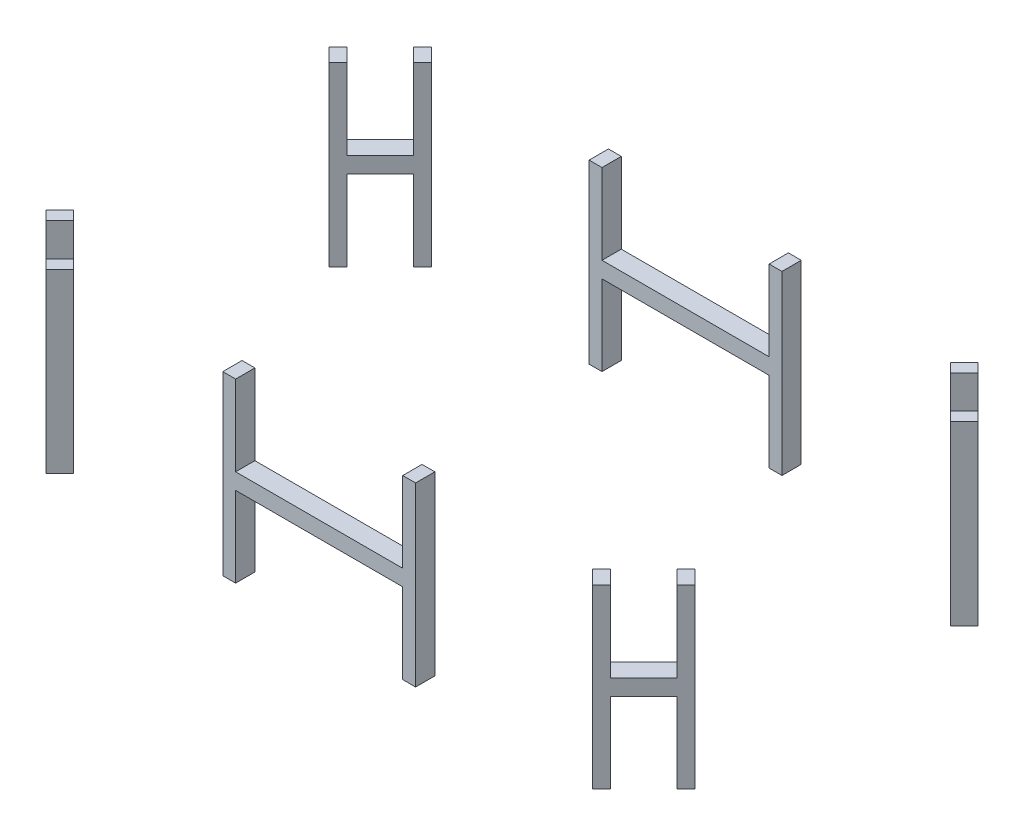
SolidWorks part; units mm, degrees
ref_plane "前视基准面" through (0, 0, 0) normal (0, 0, 1) x (1, 0, 0)
ref_plane "上视基准面" through (0, 0, 0) normal (0, 1, 0) x (1, 0, 0)
ref_plane "右视基准面" through (0, 0, 0) normal (1, 0, 0) x (0, 0, -1)
sketch "草图1" plane through (0, 0, 0) normal (0, 1, 0) x (1, 0, 0)
  line L8 (-505, 220) -> (-425, 300)
  line L12 (-425, 300) -> (-403.7868, 278.7868)
  line L13 (-403.7868, 278.7868) -> (-483.7868, 198.7868)
  line L14 (-505, 220) -> (-483.7868, 198.7868)
  line L15 (-150, 270) -> (150, 270)
  line L16 (0, 300) -> (-150, 300)
  line L17 (-150, 300) -> (-150, 270)
  line L18 (0, 300) -> (150, 300)
  line L19 (150, 300) -> (150, 270)
  line L20 (0, 0) -> (0, 106.1612) construction
  line L21 (0, 0) -> (94.5244, 0) construction
  line L22 (505, 220) -> (483.7868, 198.7868)
  line L23 (403.7868, 278.7868) -> (483.7868, 198.7868)
  line L24 (425, 300) -> (403.7868, 278.7868)
  line L25 (505, 220) -> (425, 300)
  line L26 (505, -220) -> (425, -300)
  line L27 (425, -300) -> (403.7868, -278.7868)
  line L28 (403.7868, -278.7868) -> (483.7868, -198.7868)
  line L29 (505, -220) -> (483.7868, -198.7868)
  line L30 (-150, -300) -> (-150, -270)
  line L31 (0, -300) -> (-150, -300)
  line L32 (0, -300) -> (150, -300)
  line L33 (150, -300) -> (150, -270)
  line L34 (-150, -270) -> (150, -270)
  line L35 (-505, -220) -> (-483.7868, -198.7868)
  line L36 (-403.7868, -278.7868) -> (-483.7868, -198.7868)
  line L37 (-425, -300) -> (-403.7868, -278.7868)
  line L38 (-505, -220) -> (-425, -300)
  point P3 (-505, 300)
  point P5 (505, 300)
  point P6 (505, -300)
  point P7 (-505, -300)
extrude "凸台-拉伸1" add sketch "草图1" along normal blind 275
sketch "草图2" plane through (0, 0, 300) normal (0, 0, 1) x (1, 0, 0)
  line L1 (-150, 275) -> (150, 275) construction
  line L3 (130, 275) -> (130, 150)
  line L4 (-130, 275) -> (-130, 150)
  line L5 (-130, 275) -> (130, 275)
  line L6 (130, 150) -> (-130, 150)
  line L8 (130, 0) -> (130, 125)
  line L9 (130, 125) -> (-130, 125)
  line L10 (-130, 0) -> (-130, 125)
  line L11 (-130, 0) -> (130, 0)
extrude "切除-拉伸1" cut sketch "草图2" against normal through all both and the other way through all
sketch "草图3" plane through (362.5, 0, 362.5) normal (0.7071, 0, 0.7071) x (0.7071, 0, -0.7071)
  line L1 (88.3883, 275) -> (201.5254, 275) construction
  line L2 (108.3883, 275) -> (108.3883, 150)
  line L4 (181.5254, 275) -> (181.5254, 150)
  line L5 (181.5254, 150) -> (108.3883, 150)
  line L6 (108.3883, 275) -> (181.5254, 275)
  line L8 (181.5254, 0) -> (181.5254, 125)
  line L9 (181.5254, 125) -> (108.3883, 125)
  line L10 (108.3883, 0) -> (108.3883, 125)
  line L11 (108.3883, 0) -> (181.5254, 0)
extrude "切除-拉伸2" cut sketch "草图3" against normal blind 30
sketch "草图4" plane through (362.5, 0, -362.5) normal (0.7071, 0, -0.7071) x (-0.7071, 0, -0.7071)
  line L0 (-181.5254, 275) -> (-108.3883, 275)
  line L1 (-201.5254, 275) -> (-88.3883, 275) construction
  line L2 (-181.5254, 275) -> (-181.5254, 150)
  line L3 (-201.5254, 137.5) -> (-88.3883, 137.5) construction
  line L4 (-108.3883, 275) -> (-108.3883, 150)
  line L5 (-108.3883, 150) -> (-181.5254, 150)
  line L6 (-201.5254, 275) -> (-201.5254, 0) construction
  line L7 (-88.3883, 275) -> (-88.3883, 0) construction
  line L8 (-181.5254, 0) -> (-181.5254, 125)
  line L9 (-108.3883, 125) -> (-181.5254, 125)
  line L10 (-108.3883, 0) -> (-108.3883, 125)
  line L11 (-181.5254, 0) -> (-108.3883, 0)
extrude "切除-拉伸3" cut sketch "草图4" against normal blind 30
sketch "草图5" plane through (-362.5, 0, -362.5) normal (-0.7071, 0, -0.7071) x (-0.7071, 0, 0.7071)
  line L1 (88.3883, 275) -> (201.5254, 275) construction
  line L2 (108.3883, 275) -> (108.3883, 150)
  line L4 (181.5254, 275) -> (181.5254, 150)
  line L5 (181.5254, 150) -> (108.3883, 150)
  line L6 (108.3883, 275) -> (181.5254, 275)
  line L8 (181.5254, 0) -> (181.5254, 125)
  line L9 (181.5254, 125) -> (108.3883, 125)
  line L10 (108.3883, 0) -> (108.3883, 125)
  line L11 (108.3883, 0) -> (181.5254, 0)
extrude "切除-拉伸4" cut sketch "草图5" against normal blind 30
sketch "草图6" plane through (-362.5, 0, 362.5) normal (-0.7071, 0, 0.7071) x (0.7071, 0, 0.7071)
  line L0 (-201.5254, 137.5) -> (-88.3883, 137.5) construction
  line L1 (-201.5254, 275) -> (-88.3883, 275) construction
  line L2 (-181.5254, 275) -> (-181.5254, 150)
  line L3 (-201.5254, 275) -> (-201.5254, 0) construction
  line L4 (-108.3883, 275) -> (-108.3883, 150)
  line L5 (-108.3883, 150) -> (-181.5254, 150)
  line L6 (-181.5254, 275) -> (-108.3883, 275)
  line L7 (-88.3883, 275) -> (-88.3883, 0) construction
  line L8 (-108.3883, 0) -> (-108.3883, 125)
  line L9 (-108.3883, 125) -> (-181.5254, 125)
  line L10 (-181.5254, 0) -> (-181.5254, 125)
  line L11 (-181.5254, 0) -> (-108.3883, 0)
extrude "切除-拉伸5" cut sketch "草图6" against normal blind 30
